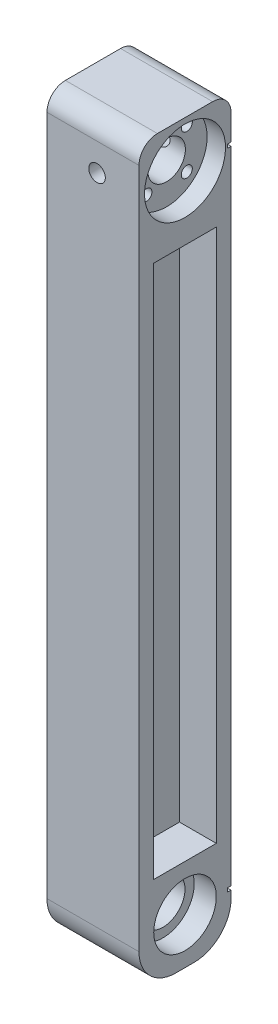
SolidWorks part; units mm, degrees
ref_plane "Alzado" through (0, 0, 0) normal (0, 0, 1) x (1, 0, 0)
ref_plane "Planta" through (0, 0, 0) normal (0, 1, 0) x (1, 0, 0)
ref_plane "Vista lateral" through (0, 0, 0) normal (1, 0, 0) x (0, 0, -1)
sketch "Croquis1" plane through (0, 0, 0) normal (0, 1, 0) x (1, 0, 0)
  line L1 (0, 0) -> (25, 0)
  line L2 (0, 0) -> (0, 25)
  line L3 (0, 25) -> (25, 25)
  line L4 (25, 0) -> (25, 25)
  dimension "D1" = 25
  dimension "D2" = 25
extrude "Saliente-Extruir1" add sketch "Croquis1" along normal blind 200
fillet "Redondeo1" radius 10 1 edges at (12.5, 0, -25)
fillet "Redondeo2" radius 10 1 edges at (12.5, 0, 0)
fillet "Redondeo3" radius 5 1 edges at (12.5, 200, 0)
fillet "Redondeo4" radius 5 1 edges at (12.5, 200, -25)
sketch "Croquis2" plane through (25, 0, 0) normal (1, 0, 0) x (0, 0, -1)
  line L0 (5, 200) -> (20, 200) construction
  line L1 (25, 195) -> (25, 10) construction
  circle A0 centre (12.5, 187.5) radius 11
  circle A1 centre (12.5, 12.5) radius 8.5
  dimension "D2" = 22
  dimension "D5" = 17
  dimension "D1" = 12.5
  dimension "D3" = 12.5
  dimension "D4" = 175
  dimension "D6" = 12.5
extrude "Cortar-Extruir1" cut sketch "Croquis2" against normal blind 6
sketch "Croquis3" plane through (0, 0, 0) normal (-1, 0, 0) x (0, 0, 1)
  line L0 (-25, 195) -> (-25, 10) construction
  line L2 (-15, 0) -> (-10, 0) construction
  circle A0 centre (-12.5, 12.5) radius 8.5
  circle A1 centre (-12.5, 187.5) radius 8.5
  dimension "D1" = 17
  dimension "D5" = 17
  dimension "D2" = 12.5
  dimension "D3" = 12.5
  dimension "D4" = 175
  dimension "D6" = 12.5
extrude "Cortar-Extruir2" cut sketch "Croquis3" against normal blind 6
sketch "Croquis9" plane through (19, 0, 0) normal (1, 0, 0) x (0, 0, -1)
  circle A0 centre (12.5, 187.5) radius 5.1
  circle A1 centre (12.5, 12.5) radius 6
  dimension "D1" = 10.2
  dimension "D2" = 12
extrude "Cortar-Extruir6" cut sketch "Croquis9" against normal blind 30
ref_plane "Plano1" through (12.5, 0, 0) normal (1, 0, 0) x (0, 0, -1)
sketch "Croquis13" plane through (0, 0, -25) normal (0, 0, -1) x (-1, 0, 0)
  line L0 (0, 195) -> (-25, 195) construction
  line L1 (-13, 189.5473) -> (-12, 189.5473)
  line L2 (-13, 189.5473) -> (-13, 184.5473)
  line L3 (-13, 184.5473) -> (-12, 184.5473)
  line L4 (-12, 189.5473) -> (-12, 184.5473)
  point P6 (-12.5, 195)
  dimension "D1" = 1
  dimension "D2" = 0.5
  dimension "D3" = 5
extrude "Cortar-Extruir8" cut sketch "Croquis13" against normal blind 1
sketch "Croquis14" plane through (19, 0, 0) normal (1, 0, 0) x (0, 0, -1)
  circle A1 centre (12.5, 187.5) radius 11
  circle A2 centre (12.5, 187.5) radius 11
  circle A3 centre (12.5, 187.5) radius 5.1
  dimension "D2" = 10.2
  dimension "D1" = 0
extrude "Saliente-Extruir3" add sketch "Croquis14" along normal blind 1
sketch "Croquis15" plane through (20, 0, 0) normal (1, 0, 0) x (0, 0, -1)
  line L1 (12.5, 187.5) -> (12.5, 175.887) construction
  line L2 (12.5, 187.5) -> (7.0199, 182.0199) construction
  circle A0 centre (12.5, 187.5) radius 7.75 construction
  circle A1 centre (17.9801, 182.0199) radius 1.5
  circle A2 centre (7.0199, 182.0199) radius 1.5
  circle A3 centre (7.0199, 192.9801) radius 1.5
  circle A4 centre (17.9801, 192.9801) radius 1.5
  point P14 (12.5, 187.5)
  dimension "D2" = 3
  dimension "D3" = 15.5
  dimension "D4" = 45
  dimension "D1" = 4
extrude "Cortar-Extruir9" cut sketch "Croquis15" against normal blind 16
sketch "Croquis16" plane through (0, 0, 0) normal (-1, 0, 0) x (0, 0, 1)
  line L0 (-14.83, 192.2518) -> (-15.7744, 195.344)
  line L1 (-17.2518, 185.17) -> (-20.344, 184.2256)
  line L2 (-20.344, 184.2256) -> (-21.0722, 181.0756)
  line L3 (-21.0722, 181.0756) -> (-18.7083, 178.8698)
  line L4 (-18.7083, 178.8698) -> (-15.6161, 179.8142)
  line L5 (-15.6161, 179.8142) -> (-14.8879, 182.9643)
  line L6 (-14.8879, 182.9643) -> (-17.2518, 185.17)
  line L7 (-17.0357, 189.8879) -> (-14.83, 192.2518)
  line L8 (-20.1858, 190.6161) -> (-17.0357, 189.8879)
  line L9 (-21.1302, 193.7083) -> (-20.1858, 190.6161)
  line L10 (-18.9244, 196.0722) -> (-21.1302, 193.7083)
  line L11 (-15.7744, 195.344) -> (-18.9244, 196.0722)
  line L12 (-7.7482, 189.83) -> (-4.656, 190.7744)
  line L13 (-10.1121, 192.0357) -> (-7.7482, 189.83)
  line L14 (-9.3839, 195.1858) -> (-10.1121, 192.0357)
  line L15 (-6.2917, 196.1302) -> (-9.3839, 195.1858)
  line L16 (-3.9278, 193.9244) -> (-6.2917, 196.1302)
  line L17 (-4.656, 190.7744) -> (-3.9278, 193.9244)
  line L18 (-10.17, 182.7482) -> (-9.2256, 179.656)
  line L19 (-7.9643, 185.1121) -> (-10.17, 182.7482)
  line L20 (-4.8142, 184.3839) -> (-7.9643, 185.1121)
  line L21 (-3.8698, 181.2917) -> (-4.8142, 184.3839)
  line L22 (-6.0756, 178.9278) -> (-3.8698, 181.2917)
  line L23 (-9.2256, 179.656) -> (-6.0756, 178.9278)
  circle A0 centre (-17.9801, 182.0199) radius 2.8 construction
  circle A1 centre (-12.5, 187.5) radius 7.75 construction
  circle A2 centre (-12.5, 187.5) radius 8.5 construction
  point P33 (-12.5, 187.5)
  dimension "D2" = 5.6
  dimension "D1" = 4
extrude "Cortar-Extruir10" cut sketch "Croquis16" against normal blind 11
sketch "Croquis18" plane through (25, 0, 0) normal (1, 0, 0) x (0, 0, -1)
  line L0 (25, 195) -> (25, 10) construction
  line L1 (25, 188) -> (24, 188)
  line L2 (25, 188) -> (25, 187)
  line L3 (25, 187) -> (24, 187)
  line L4 (24, 188) -> (24, 187)
  line L6 (25, 13) -> (24, 13)
  line L7 (25, 13) -> (25, 12)
  line L8 (25, 12) -> (24, 12)
  line L9 (24, 13) -> (24, 12)
  circle A0 centre (12.5, 12.5) radius 8.5 construction
  circle A1 centre (12.5, 187.5) radius 5.3994 construction
  point P10 (24, 12.5)
  point P17 (24, 187.5)
  dimension "D1" = 1
  dimension "D2" = 1
  dimension "D3" = 1
  dimension "D4" = 1
extrude "Cortar-Extruir12" cut sketch "Croquis18" against normal up to surface (25 mm away) up to face at (0, 12.5, -4)
sketch "Croquis19" plane through (25, 0, 0) normal (1, 0, 0) x (0, 0, -1)
  line L1 (21, 25) -> (4, 25)
  line L2 (21, 25) -> (21, 170)
  line L3 (21, 170) -> (4, 170)
  line L4 (4, 25) -> (4, 170)
  line L6 (5, 200) -> (20, 200) construction
  line L7 (10, 0) -> (15, 0) construction
  line L8 (25, 187) -> (25, 13) construction
  line L9 (0, 195) -> (0, 10) construction
  dimension "D1" = 25
  dimension "D2" = 30
  dimension "D3" = 4
  dimension "D4" = 4
extrude "Cortar-Extruir13" cut sketch "Croquis19" against normal blind 10
sketch "Croquis20" plane through (0, 0, 0) normal (-1, 0, 0) x (0, 0, 1)
  line L0 (-15, 0) -> (-10, 0) construction
  line L1 (-4, 25) -> (-21, 25)
  line L2 (-4, 25) -> (-4, 170)
  line L3 (-4, 170) -> (-21, 170)
  line L4 (-21, 25) -> (-21, 170)
  line L5 (-20, 200) -> (-5, 200) construction
  line L6 (-25, 187) -> (-25, 13) construction
  line L7 (0, 195) -> (0, 10) construction
  point P6 (-12.5, 0)
  dimension "D1" = 25
  dimension "D2" = 30
  dimension "D3" = 4
  dimension "D4" = 4
extrude "Cortar-Extruir14" cut sketch "Croquis20" against normal blind 10
sketch "Croquis12" plane through (0, 0, -25) normal (0, 0, -1) x (-1, 0, 0)
  line L0 (-25, 200) -> (-25, 0) construction
  line L1 (-25, 200) -> (0, 200) construction
  circle A0 centre (-13.6, 187.5) radius 2.25
  dimension "D1" = 4.5
  dimension "D2" = 11.4
  dimension "D3" = 12.5
extrude "Cortar-Extruir7" cut sketch "Croquis12" against normal through all
